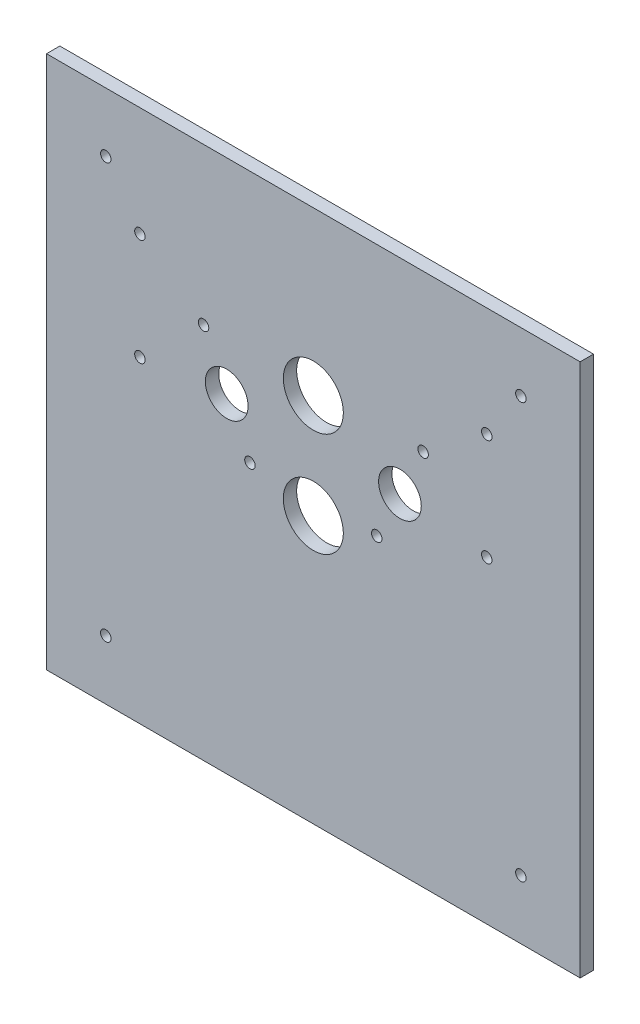
SolidWorks part; units mm, degrees
material "6061-T6 (SS)"
ref_plane "Front Plane" through (0, 0, 0) normal (0, 0, 1) x (1, 0, 0)
ref_plane "Top Plane" through (0, 0, 0) normal (0, 1, 0) x (1, 0, 0)
ref_plane "Right Plane" through (0, 0, 0) normal (1, 0, 0) x (0, 0, -1)
sketch "Sketch1" plane through (0, 0, 0) normal (0, 0, 1) x (1, 0, 0)
  line L0 (0, 49.5808) -> (0, 0) construction
  line L1 (-41.222, 29.6882) -> (0, 49.5808) construction
  line L2 (0, 63.8683) -> (0, 127) construction
  line L3 (-52.2611, 52.5639) -> (-30.1828, 6.8125) construction
  line L4 (-127, -127) -> (127, -127)
  line L5 (-127, -127) -> (-127, 127)
  line L6 (-127, 127) -> (127, 127)
  line L7 (127, -127) -> (127, 127)
  line L8 (-127, -127) -> (127, 127) construction
  line L9 (-127, 127) -> (127, -127) construction
  line L10 (0, -14.2875) -> (0, -127) construction
  line L11 (-41.222, 29.6882) -> (0, 0) construction
  line L13 (-88.9, 17.8308) -> (88.9, 17.8308) construction
  line L14 (-88.9, 17.8308) -> (-88.9, 81.3308) construction
  line L15 (-88.9, 81.3308) -> (88.9, 81.3308) construction
  line L16 (88.9, 17.8308) -> (88.9, 81.3308) construction
  line L17 (-88.9, 17.8308) -> (88.9, 81.3308) construction
  line L18 (-88.9, 81.3308) -> (88.9, 17.8308) construction
  circle A0 centre (0, 0) radius 114.3 construction
  circle A1 centre (0, 0) radius 38.1 construction
  circle A2 centre (0, 49.5808) radius 11.43 construction
  circle A3 centre (0, 49.5808) radius 38.1 construction
  circle A4 centre (-41.222, 29.6882) radius 7.62 construction
  circle A6 centre (-41.222, 29.6882) radius 10.16
  circle A8 centre (-41.222, 29.6882) radius 25.4 construction
  circle A9 centre (-41.222, 29.6882) radius 33.02 construction
  circle A12 centre (-41.222, 29.6882) radius 8.89 construction
  circle A13 centre (0, 0) radius 39.37 construction
  circle A14 centre (0, 49.5808) radius 14.2875
  circle A15 centre (0, 0) radius 127 construction
  circle A16 centre (-98.7828, 98.7828) radius 12.7 construction
  circle A17 centre (-98.7828, 98.7828) radius 6.35 construction
  circle A18 centre (0, 0) radius 14.2875
  circle A19 centre (-98.7828, -98.7828) radius 12.7 construction
  circle A20 centre (-98.7828, -98.7828) radius 6.35 construction
  circle A21 centre (0, 49.5808) radius 39.37 construction
  circle A22 centre (0, 49.5808) radius 12.7 construction
  circle A23 centre (41.222, 29.6882) radius 10.16
  circle A24 centre (-82.55, 74.9808) radius 6.35 construction
  circle A25 centre (82.55, 74.9808) radius 6.35 construction
  circle A26 centre (82.55, 24.1808) radius 6.35 construction
  circle A27 centre (-82.55, 24.1808) radius 6.35 construction
  point P24 (-41.222, 29.6882)
  point P27 (-98.7828, 98.7828)
  point P32 (-98.7828, -98.7828)
  point P33 (-52.2611, 52.5639)
  point P34 (-30.1828, 6.8125)
  point P40 (52.2611, 52.5639)
  point P41 (30.1828, 6.8125)
  point P42 (98.7828, -98.7828)
  point P43 (98.7828, 98.7828)
  point P59 (82.55, 24.1808)
  point P60 (-82.55, 24.1808)
  point P61 (-82.55, 74.9808)
  point P65 (82.55, 74.9808)
  dimension "D1" = 228.6
  dimension "D2" = 76.2
  dimension "D3" = 22.86
  dimension "D5" = 76.2
  dimension "D6" = 15.24
  dimension "D7" = 28.575
  dimension "D8" = 20.32
  dimension "D9" = 25.4
  dimension "D12" = 66.04
  dimension "D13" = 28.575
  dimension "D14" = 50.8
  dimension "D15" = 25.4
  dimension "D18" = 78.74
  dimension "D19" = 17.78
  dimension "D11" = 12.7
  dimension "D20" = 12.7
  dimension "D21" = 78.74
  dimension "D22" = 25.4
  dimension "D26" = 12.7
  dimension "D27" = 12.7
  dimension "D28" = 12.7
  dimension "D29" = 12.7
  dimension "D4" = 49.5808
  dimension "D10" = 45.7708
  dimension "D16" = 254
  dimension "D17" = 254
  dimension "D23" = 50.8
  dimension "D24" = 177.8
  dimension "D25" = 63.5
extrude "Boss-Extrude2" add sketch "Sketch1" along normal blind 6.35 contours L4 L7 L6 L5 A6 A14 A18 A23
hole_wizard "#9 (0.196) Diameter Hole1" positions "Sketch4" profile "Sketch5" hole size "#9" standard "ANSI Inch" end condition through all
sketch "Sketch4" plane through (0, 0, 0) normal (0, 0, -1) x (-1, 0, 0)
  point P0 (-98.7828, 98.7828)
  point P3 (-52.2611, 52.5639)
  point P6 (-30.1828, 6.8125)
  point P9 (30.1828, 6.8125)
  point P12 (52.2611, 52.5639)
  point P15 (98.7828, 98.7828)
  point P18 (98.7828, -98.7828)
  point P21 (-98.7828, -98.7828)
  point P25 (-82.55, 74.9808)
  point P28 (-82.55, 24.1808)
  point P31 (82.55, 74.9808)
  point P34 (82.55, 24.1808)
sketch "Sketch5" plane through (98.7828, 98.7828, 0) normal (1, 0, 0) x (0, 1, 0)
  line L0 (0, 0) -> (0, 6.35)
  line L1 (0, 6.35) -> (2.4892, 6.35)
  line L2 (2.4892, 6.35) -> (2.4892, 0)
  line L5 (2.4892, 0) -> (0, 0)
  line L11 (0, -6.35) -> (0, 107.95) construction
  dimension "Thru Hole Dia." = 4.9784
  dimension "Thru Hole Depth" = 6.35
